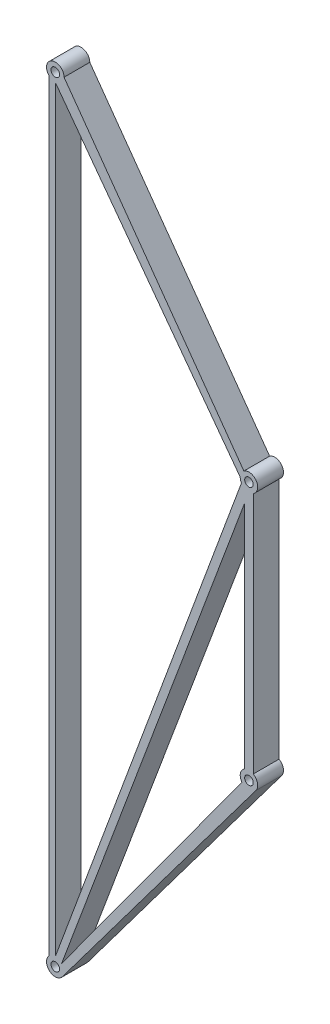
SolidWorks part; units mm, degrees
material "ASTM A500 Steel"
ref_plane "Front Plane" through (0, 0, 0) normal (1, 0, 0) x (0, 1, 0)
ref_plane "Top Plane" through (0, 0, 0) normal (0, 0, 1) x (0, 1, 0)
ref_plane "Right Plane" through (0, 0, 0) normal (0, 1, 0) x (-1, 0, 0)
sketch "Sketch9" plane through (0, 0, 0) normal (0, 0, 1) x (0, 1, 0)
  line L0 (-386.45, 300) -> (393.0404, 11.6261)
  line L1 (-390.6818, 290.1626) -> (368.559, 6.6801)
  line L2 (400, 13.55) -> (786.45, 300)
  line L3 (800, 286.45) -> (411.0165, 7.8892)
  line L4 (11.7889, 6.6801) -> (368.559, 6.6801)
  line L5 (11.7889, -6.6801) -> (388.2111, -6.6801)
  line L6 (-390.6818, 309.8374) -> (790.6818, 309.8374)
  line L7 (-386.45, 300) -> (786.45, 300)
  line L8 (-408.13, 289.16) -> (-8.13, -10.84)
  line L9 (-8.13, 10.84) -> (-390.6818, 290.1626)
  arc A0 (-8.13, -10.84) -> (11.7889, -6.6801) centre (0, 0) ccw
  arc A2 (800, 286.45) -> (790.6818, 309.8374) centre (800, 300) ccw
  arc A3 (388.2111, -6.6801) -> (411.0165, 7.8892) centre (400, 0) ccw
  arc A4 (-390.6818, 309.8374) -> (-408.13, 289.16) centre (-400, 300) ccw
  arc A5 (11.7889, 6.6801) -> (-8.13, 10.84) centre (0, 0) ccw
  arc A6 (400, 13.55) -> (393.0404, 11.6261) centre (400, 0) ccw
  circle A7 centre (-400, 300) radius 6.65
  circle A8 centre (0, 0) radius 6.65
  circle A9 centre (400, 0) radius 6.65
  circle A10 centre (800, 300) radius 6.65
  dimension "D1" = 13.3
  dimension "D4" = 400
  dimension "D2" = 300
  dimension "D3" = 400
  dimension "D5" = 400
extrude "Boss-Extrude1" add sketch "Sketch9" along normal blind 39.9
